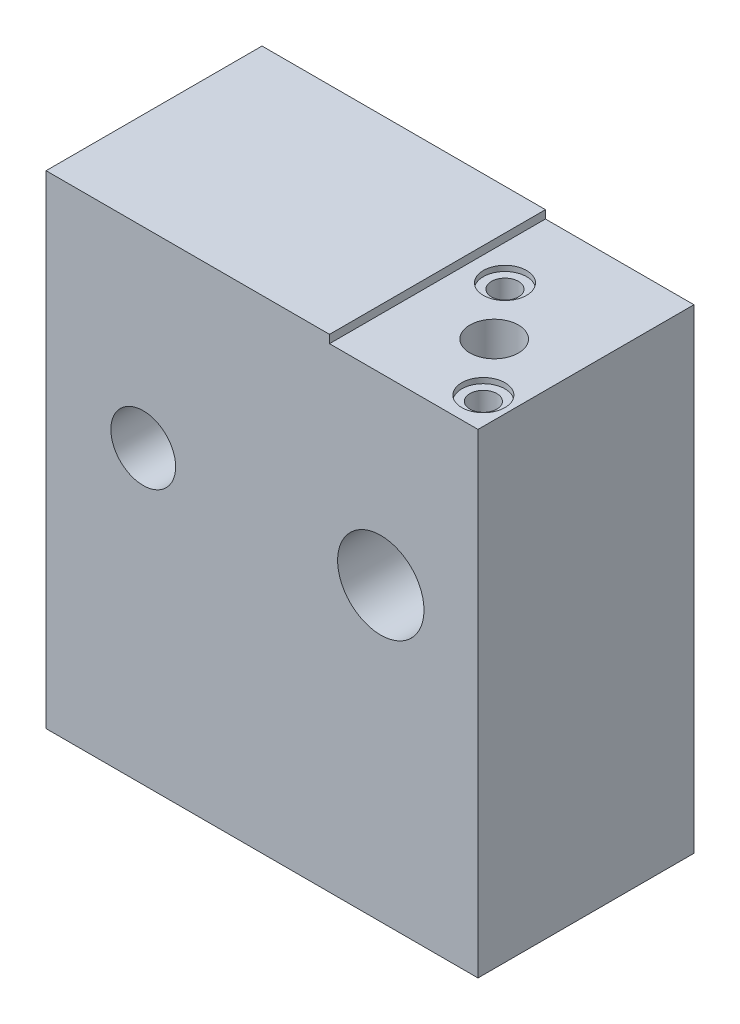
SolidWorks part; units mm, degrees
ref_plane "前视基准面" through (0, 0, 0) normal (0, 0, 1) x (1, 0, 0)
ref_plane "上视基准面" through (0, 0, 0) normal (0, 1, 0) x (1, 0, 0)
ref_plane "右视基准面" through (0, 0, 0) normal (1, 0, 0) x (0, 0, -1)
sketch "草图1" plane through (0, 0, 0) normal (0, 1, 0) x (1, 0, 0)
  line L1 (-40, -20) -> (40, -20)
  line L2 (-40, -20) -> (-40, 20)
  line L3 (-40, 20) -> (40, 20)
  line L4 (40, -20) -> (40, 20)
  line L5 (-40, -20) -> (40, 20) construction
  line L6 (-40, 20) -> (40, -20) construction
  point P0 (0, 0)
  dimension "D1" = 40
  dimension "D2" = 80
extrude "凸台-拉伸1" add sketch "草图1" along normal blind 89.5
sketch "草图2" plane through (0, 0, 20) normal (0, 0, 1) x (1, 0, 0)
  line L1 (40, 89.5) -> (12.5, 89.5)
  line L2 (40, 89.5) -> (40, 88)
  line L3 (40, 88) -> (12.5, 88)
  line L4 (12.5, 89.5) -> (12.5, 88)
  dimension "D1" = 27.5
  dimension "D2" = 1.5
extrude "切除-拉伸1" cut sketch "草图2" against normal blind 46
sketch "草图3" plane through (0, 0, 20) normal (0, 0, 1) x (1, 0, 0)
  line L0 (-40, 89.5) -> (-40, 0) construction
  line L2 (-40, 0) -> (40, 0) construction
  line L4 (0, 26.2225) -> (0, 71.5522) construction
  circle A0 centre (-22, 54) radius 6
  circle A2 centre (22, 54) radius 8
  dimension "D3" = 12
  dimension "D4" = 16
  dimension "D1" = 18
  dimension "D2" = 54
extrude "切除-拉伸2" cut sketch "草图3" against normal blind 46
sketch "草图4" plane through (0, 88, 0) normal (0, 1, 0) x (1, 0, 0)
  line L0 (12.5, -20) -> (40, -20) construction
  line L1 (40, 20) -> (40, -20) construction
  circle A0 centre (35, -14) radius 2.5
  circle A1 centre (19, 6) radius 2.5
  circle A2 centre (27, -4) radius 4.5
  dimension "D1" = 5
  dimension "D2" = 5
  dimension "D9" = 9
  dimension "D3" = 6
  dimension "D4" = 5
  dimension "D5" = 20
  dimension "D6" = 16
  dimension "D7" = 10
  dimension "D8" = 8
extrude "切除-拉伸3" cut sketch "草图4" against normal blind 15
sketch "草图5" plane through (0, 88, 0) normal (0, 1, 0) x (1, 0, 0)
  circle A0 centre (19, 6) radius 4
  circle A1 centre (35, -14) radius 4
  dimension "D1" = 8
  dimension "D2" = 8
extrude "切除-拉伸4" cut sketch "草图5" against normal blind 1
